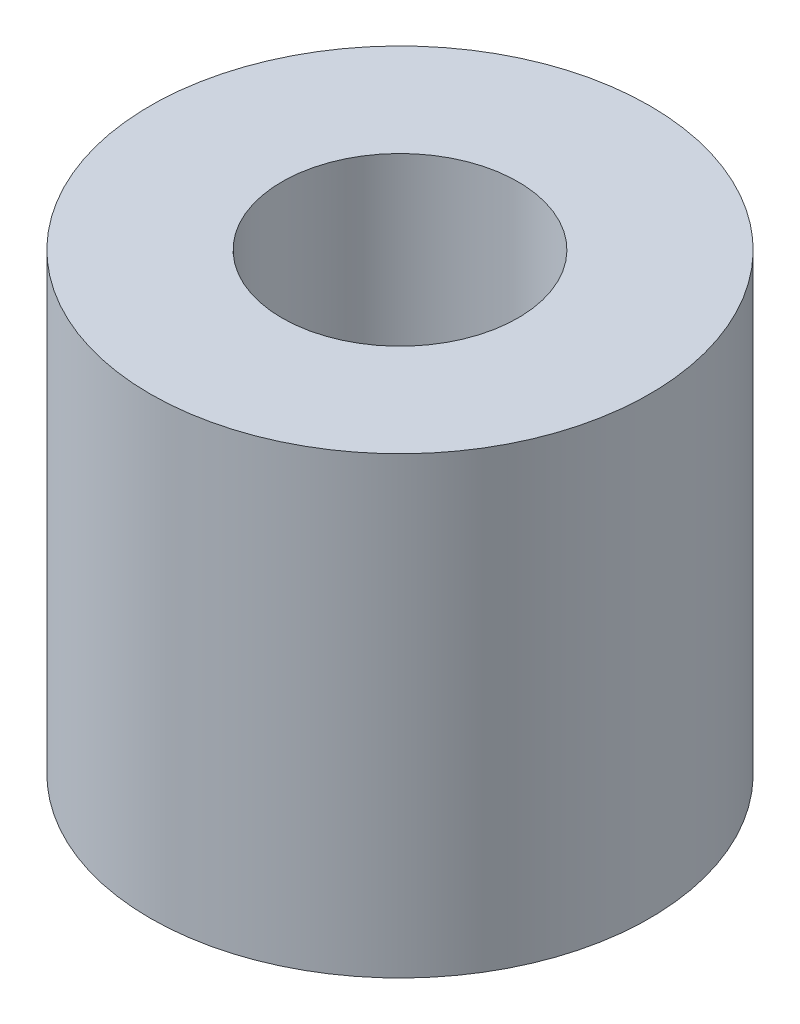
SolidWorks part; units mm, degrees
ref_plane "前视基准面" through (0, 0, 0) normal (0, 0, 1) x (1, 0, 0)
ref_plane "上视基准面" through (0, 0, 0) normal (0, 1, 0) x (1, 0, 0)
ref_plane "右视基准面" through (0, 0, 0) normal (1, 0, 0) x (0, 0, -1)
sketch "草图1" plane through (0, 0, 0) normal (0, 1, 0) x (1, 0, 0)
  circle A0 centre (0, 0) radius 5.5
  circle A1 centre (0, 0) radius 2.6
  dimension "D1" = 11
  dimension "D2" = 5.2
extrude "凸台-拉伸1" add sketch "草图1" along normal blind 10
